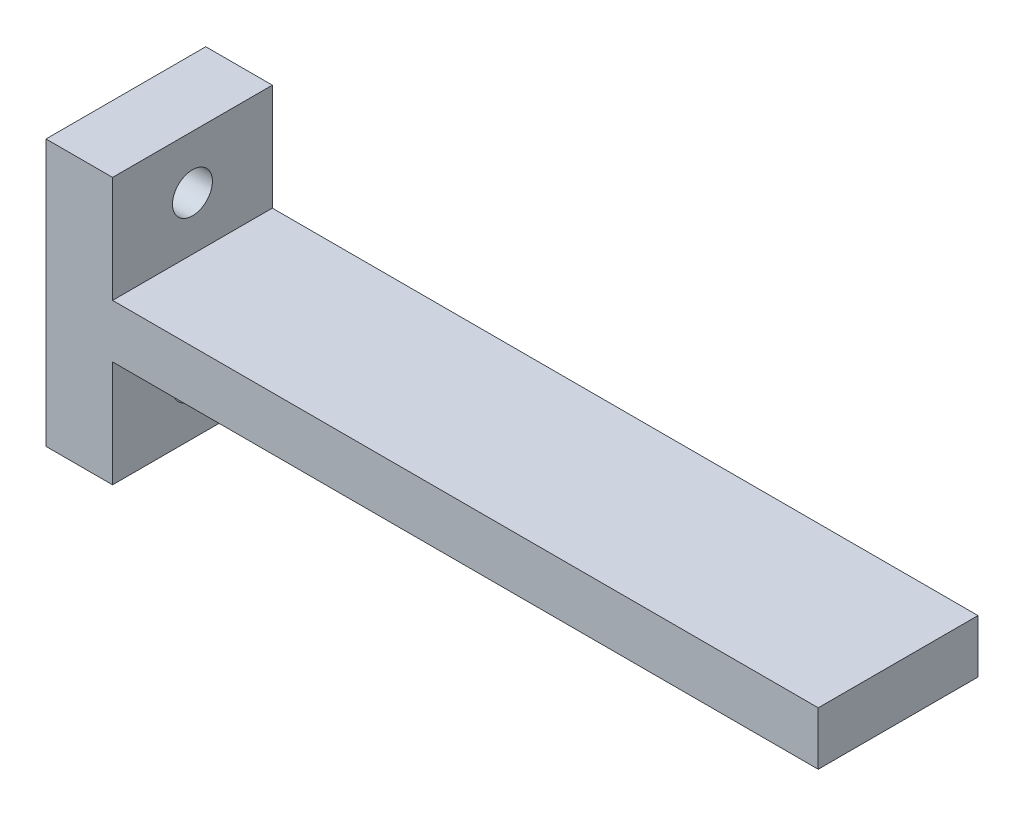
SolidWorks part; units mm, degrees
material "1350 合金"
ref_plane "前视基准面" through (0, 0, 0) normal (0, 0, 1) x (1, 0, 0)
ref_plane "上视基准面" through (0, 0, 0) normal (0, 1, 0) x (1, 0, 0)
ref_plane "右视基准面" through (0, 0, 0) normal (1, 0, 0) x (0, 0, -1)
sketch "草图1" plane through (0, 0, 0) normal (0, 1, 0) x (1, 0, 0)
  line L1 (-26.5, 6) -> (26.5, 6)
  line L2 (-26.5, 6) -> (-26.5, -6)
  line L3 (-26.5, -6) -> (26.5, -6)
  line L4 (26.5, 6) -> (26.5, -6)
  point P4 (26.5, 0)
  point P6 (0, 6)
  dimension "D1" = 12
  dimension "D2" = 53
extrude "凸台-拉伸1" add sketch "草图1" along normal mid plane 4
sketch "草图2" plane through (-26.5, 0, 0) normal (-1, 0, 0) x (0, 0, 1)
  line L1 (-6, 10) -> (6, 10)
  line L2 (-6, 10) -> (-6, -10)
  line L3 (-6, -10) -> (6, -10)
  line L4 (6, 10) -> (6, -10)
  circle A0 centre (0, 6) radius 1.5
  circle A1 centre (0, -6) radius 1.5
  point P4 (-6, 0)
  point P8 (0, 10)
  dimension "D3" = 3
  dimension "D1" = 20
  dimension "D2" = 12
  dimension "D4" = 12
  dimension "D5" = 6
extrude "凸台-拉伸2" add sketch "草图2" along normal blind 5
